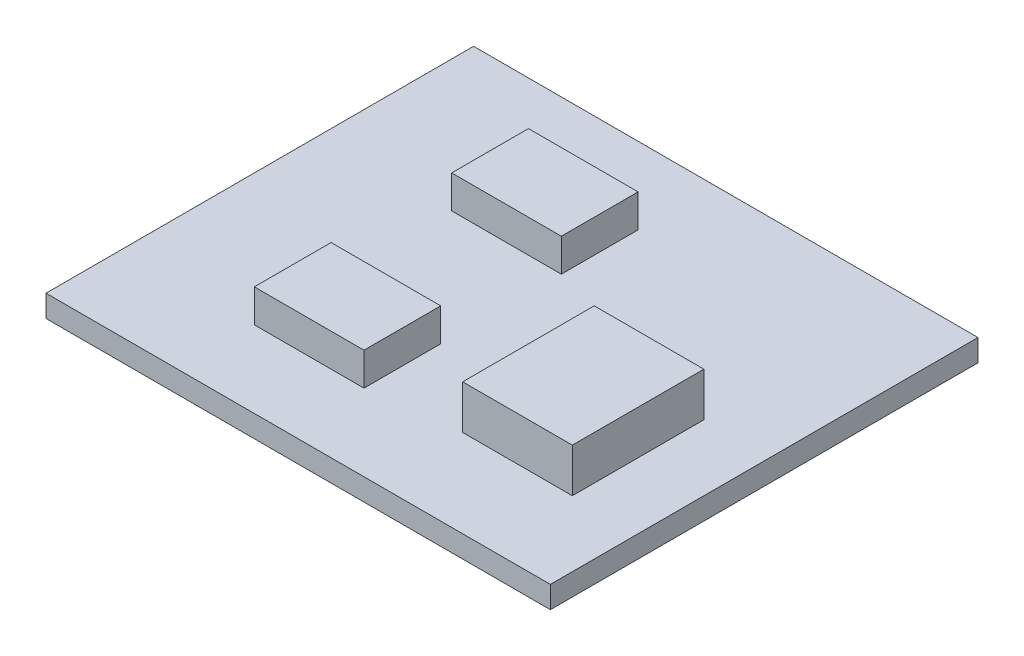
SolidWorks part; units mm, degrees
ref_plane "Ebene vorne" through (0, 0, 0) normal (0, 0, 1) x (1, 0, 0)
ref_plane "Ebene oben" through (0, 0, 0) normal (0, 1, 0) x (1, 0, 0)
ref_plane "Ebene rechts" through (0, 0, 0) normal (1, 0, 0) x (0, 0, -1)
sketch "Skizze1" plane through (0, 0, 0) normal (0, 1, 0) x (1, 0, 0)
  line L1 (0, 0) -> (23, 0)
  line L2 (0, 0) -> (0, 19.5)
  line L3 (0, 19.5) -> (23, 19.5)
  line L4 (23, 0) -> (23, 19.5)
  dimension "D1" = 23
  dimension "D2" = 19.5
extrude "Aufsatz-Linear austragen1" add sketch "Skizze1" along normal blind 1
sketch "Skizze2" plane through (0, 1, 0) normal (0, 1, 0) x (1, 0, 0)
  line L0 (23, 0) -> (23, 19.5) construction
  line L1 (15, 10) -> (20, 10)
  line L2 (15, 10) -> (15, 4)
  line L3 (15, 4) -> (20, 4)
  line L4 (20, 10) -> (20, 4)
  line L13 (0, 0) -> (23, 0) construction
  dimension "D1" = 6
  dimension "D2" = 5
  dimension "D3" = 3
  dimension "D4" = 4
extrude "Aufsatz-Linear austragen2" add sketch "Skizze2" along normal blind 2
sketch "Skizze3" plane through (0, 1, 0) normal (0, 1, 0) x (1, 0, 0)
  line L0 (23, 19.5) -> (0, 19.5) construction
  line L1 (6, 16) -> (11, 16)
  line L2 (6, 16) -> (6, 12.5)
  line L3 (6, 12.5) -> (11, 12.5)
  line L4 (11, 16) -> (11, 12.5)
  line L5 (6, 7) -> (11, 7)
  line L6 (6, 7) -> (6, 3.5)
  line L7 (6, 3.5) -> (11, 3.5)
  line L8 (11, 7) -> (11, 3.5)
  line L9 (0, 0) -> (23, 0) construction
  line L10 (0, 19.5) -> (0, 0) construction
  dimension "D1" = 5
  dimension "D2" = 3.5
  dimension "D3" = 5
  dimension "D4" = 3.5
  dimension "D5" = 3.5
  dimension "D6" = 3.5
  dimension "D7" = 6
  dimension "D8" = 6
extrude "Aufsatz-Linear austragen3" add sketch "Skizze3" along normal blind 1.5
ref_plane "Ebene1" through (0, 0.5, 0) normal (0, 1, 0) x (1, 0, 0)
mirror "Spiegeln1" about plane through (0, 0.5, 0) normal (0, 1, 0) of "Aufsatz-Linear austragen3"
sketch "Skizze4" plane through (0, 0, 0) normal (0, -1, 0) x (1, 0, 0)
  line L0 (0, 0) -> (23, 0) construction
  line L1 (18.5, -9) -> (16, -9)
  line L2 (18.5, -9) -> (18.5, -7.5)
  line L3 (18.5, -7.5) -> (16, -7.5)
  line L4 (16, -9) -> (16, -7.5)
  line L5 (18.5, -6) -> (16, -6)
  line L6 (18.5, -6) -> (18.5, -4.5)
  line L7 (18.5, -4.5) -> (16, -4.5)
  line L8 (16, -6) -> (16, -4.5)
  line L12 (23, 0) -> (23, -19.5) construction
  dimension "D1" = 4.5
  dimension "D2" = 1.5
  dimension "D3" = 1.5
  dimension "D4" = 1.5
  dimension "D5" = 2.5
  dimension "D6" = 2.5
  dimension "D7" = 4.5
  dimension "D8" = 4.5
extrude "Aufsatz-Linear austragen4" add sketch "Skizze4" along normal blind 2
